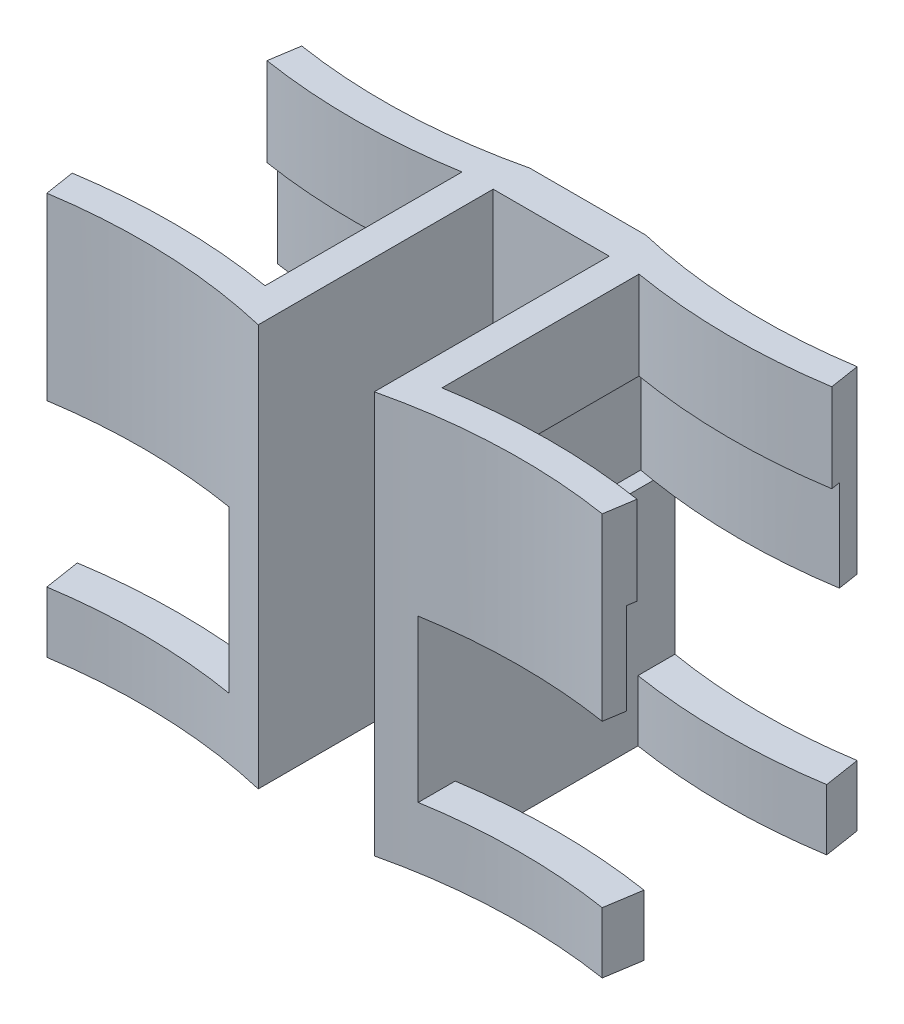
SolidWorks part; units mm, degrees
ref_plane "Front Plane" through (0, 0, 0) normal (0, 0, 1) x (1, 0, 0)
ref_plane "Top Plane" through (0, 0, 0) normal (0, 1, 0) x (1, 0, 0)
ref_plane "Right Plane" through (0, 0, 0) normal (1, 0, 0) x (0, 0, -1)
sketch "Sketch1" plane through (0, 0, 0) normal (0, 1, 0) x (1, 0, 0)
  line L0 (-6, -1.2833) -> (-6, -31.2833)
  line L1 (0, 0) -> (0, -38.5665)
  line L2 (-37, -1.2833) -> (-36.07, 4.6442)
  line L3 (-37, -31.2833) -> (-36.07, -37.2107)
  line L4 (0, 6) -> (19.05, 6)
  line L5 (25.05, -1.2833) -> (25.05, -31.2833)
  line L6 (19.05, 0) -> (19.05, -38.5665)
  line L7 (56.05, -1.2833) -> (55.12, 4.6442)
  line L8 (56.05, -31.2833) -> (55.12, -37.2107)
  line L9 (0, 0) -> (19.05, 0)
  line L10 (0, 6) -> (0, -38.5665) construction
  line L11 (19.05, 6) -> (19.05, -38.5665) construction
  arc A0 (-6, -1.2833) -> (-37, -1.2833) centre (-21.5, 97.5082) cw
  arc A1 (-6, -31.2833) -> (-37, -31.2833) centre (-21.5, -130.0747) ccw
  arc A2 (0, 6) -> (-36.07, 4.6442) centre (-21.5, 97.5082) cw
  arc A3 (0, -38.5665) -> (-36.07, -37.2107) centre (-21.5, -130.0747) ccw
  arc A4 (25.05, -1.2833) -> (56.05, -1.2833) centre (40.55, 97.5082) ccw
  arc A5 (25.05, -31.2833) -> (56.05, -31.2833) centre (40.55, -130.0747) cw
  arc A6 (19.05, 6) -> (55.12, 4.6442) centre (40.55, 97.5082) ccw
  arc A7 (19.05, -38.5665) -> (55.12, -37.2107) centre (40.55, -130.0747) cw
  dimension "D1" = 100
  dimension "D2" = 31
  dimension "D3" = 30
  dimension "D4" = 31
  dimension "D5" = 31
  dimension "D7" = 31
  dimension "D9" = 30
  dimension "D10" = 19.05
  dimension "D11" = 6
  dimension "D6" = 6
  dimension "D8" = 6
extrude "Boss-Extrude1" add sketch "Sketch1" along normal blind 66
sketch "Sketch2" plane through (0, 66, 0) normal (0, 1, 0) x (1, 0, 0)
  line L12 (-6, -1.2833) -> (-6, -31.2833)
  line L13 (25.05, -1.2833) -> (25.05, -31.2833)
  line L14 (56.05, -1.2833) -> (56.05, -31.2833)
  line L15 (-37, -1.2833) -> (-37, -31.2833)
  line L16 (-5, -0.1071) -> (-5, -32.4594)
  line L17 (-38, -0.1071) -> (-38, -32.4594)
  line L18 (57.05, -0.1071) -> (57.05, -32.4594)
  line L19 (24.05, -0.1071) -> (24.05, -32.4594)
  arc A24 (-37, -1.2833) -> (-6, -1.2833) centre (-21.5, 97.5082) ccw
  arc A25 (-37, -31.2833) -> (-6, -31.2833) centre (-21.5, -130.0747) cw
  arc A26 (25.05, -1.2833) -> (56.05, -1.2833) centre (40.55, 97.5082) ccw
  arc A27 (25.05, -31.2833) -> (56.05, -31.2833) centre (40.55, -130.0747) cw
  arc A28 (56.05, -31.2833) -> (25.05, -31.2833) centre (40.55, -130.0747) ccw construction
  arc A29 (-38, -0.1071) -> (-5, -0.1071) centre (-21.5, 97.5082) ccw
  arc A30 (-38, -32.4594) -> (-5, -32.4594) centre (-21.5, -130.0747) cw
  arc A31 (24.05, -32.4594) -> (57.05, -32.4594) centre (40.55, -130.0747) cw
  arc A32 (24.05, -0.1071) -> (57.05, -0.1071) centre (40.55, 97.5082) ccw
  dimension "D1" = 100
  dimension "D2" = 1
  dimension "D3" = 1
extrude "Cut-Extrude1" cut sketch "Sketch2" against normal blind 15
sketch "Sketch3" plane through (0, 51, 0) normal (0, 1, 0) x (1, 0, 0)
  line L0 (-37, -1.2833) -> (-37, -31.2833)
  line L1 (-6, -1.2833) -> (-6, -31.2833)
  line L2 (25.05, -1.2833) -> (25.05, -31.2833)
  line L3 (56.05, -1.2833) -> (56.05, -31.2833)
  line L4 (-3.5, 1.6841) -> (-3.5, -34.2506)
  line L5 (-39.5, 1.6841) -> (-39.5, -34.2506)
  line L6 (58.55, 1.6841) -> (58.55, -34.2506)
  line L7 (22.55, 1.6841) -> (22.55, -34.2506)
  arc A0 (-37, -1.2833) -> (-6, -1.2833) centre (-21.5, 97.5082) ccw
  arc A1 (-37, -31.2833) -> (-6, -31.2833) centre (-21.5, -130.0747) cw
  arc A2 (25.05, -1.2833) -> (56.05, -1.2833) centre (40.55, 97.5082) ccw
  arc A3 (25.05, -31.2833) -> (56.05, -31.2833) centre (40.55, -130.0747) cw
  arc A4 (-39.5, -34.2506) -> (-3.5, -34.2506) centre (-21.5, -130.0747) cw
  arc A5 (-39.5, 1.6841) -> (-3.5, 1.6841) centre (-21.5, 97.5082) ccw
  arc A6 (22.55, -34.2506) -> (58.55, -34.2506) centre (40.55, -130.0747) cw
  arc A7 (22.55, 1.6841) -> (58.55, 1.6841) centre (40.55, 97.5082) ccw
  dimension "D1" = 100
  dimension "D2" = 2.5
extrude "Cut-Extrude2" cut sketch "Sketch3" against normal blind 15 from offset 0.5
sketch "Sketch4" plane through (-6, 0, 0) normal (-1, 0, 0) x (0, 0, 1)
  line L0 (-6, 36.5) -> (38.5665, 36.5)
  line L1 (31.2833, 36.5) -> (1.2833, 36.5) construction
  line L2 (38.5665, 36.5) -> (38.5665, 10)
  line L3 (38.5665, 10) -> (-6, 10)
  line L4 (-6, 10) -> (-6, 36.5)
  line L5 (-6, 66) -> (-6, 0) construction
  line L6 (38.5665, 66) -> (38.5665, 0) construction
  line L7 (1.2833, 0) -> (31.2833, 0) construction
  dimension "D1" = 10
extrude "Cut-Extrude3" cut sketch "Sketch4" along normal through all
sketch "Sketch5" plane through (25.05, 0, 0) normal (1, 0, 0) x (0, 0, -1)
  line L0 (-38.5665, 36.5) -> (6, 36.5)
  line L1 (6, 36.5) -> (6, 10)
  line L2 (6, 10) -> (-38.5665, 10)
  line L3 (-38.5665, 10) -> (-38.5665, 36.5)
  line L4 (-1.2833, 36.5) -> (-31.2833, 36.5) construction
  line L5 (-38.5665, 66) -> (-38.5665, 0) construction
  line L6 (6, 66) -> (6, 0) construction
  line L7 (-31.2833, 0) -> (-1.2833, 0) construction
  dimension "D1" = 10
extrude "Cut-Extrude4" cut sketch "Sketch5" along normal through all
